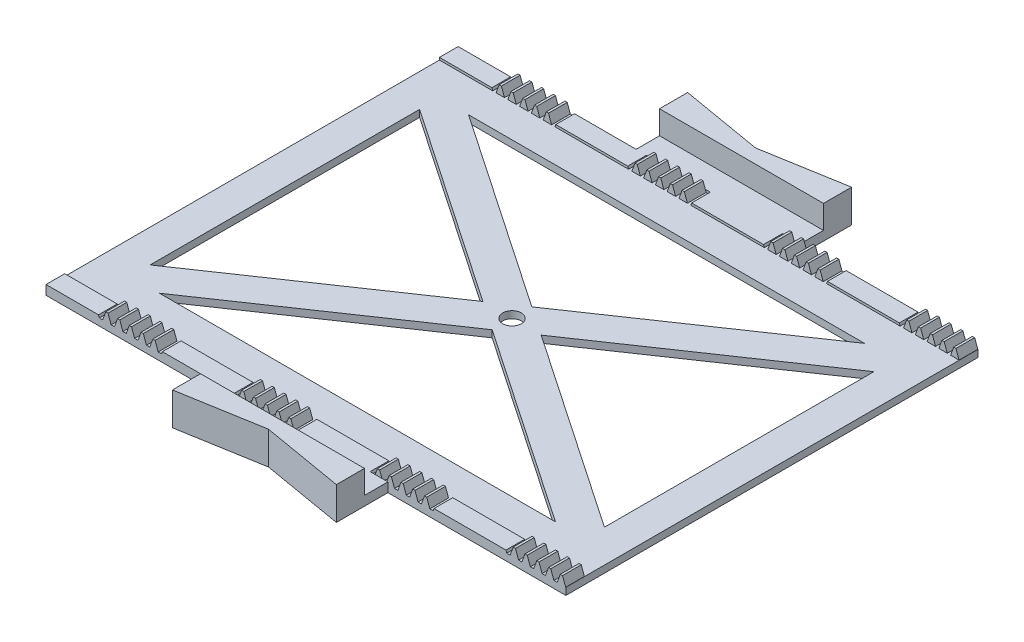
SolidWorks part; units mm, degrees
ref_plane "Front Plane" through (0, 0, 0) normal (0, 0, 1) x (1, 0, 0)
ref_plane "Top Plane" through (0, 0, 0) normal (0, 1, 0) x (1, 0, 0)
ref_plane "Right Plane" through (0, 0, 0) normal (1, 0, 0) x (0, 0, -1)
sketch "Sketch1" plane through (0, 0, 0) normal (0, 1, 0) x (1, 0, 0)
  line L0 (-17.5, -49) -> (-17.5, -44)
  line L1 (55.5, -44) -> (17.5, -44)
  line L2 (55.5, -44) -> (55.5, 44)
  line L3 (55.5, 44) -> (17.5, 44)
  line L4 (-55.5, -44) -> (-55.5, 44)
  line L5 (55.5, -44) -> (-55.5, 44) construction
  line L6 (55.5, 44) -> (-55.5, -44) construction
  line L7 (-17.5, -49) -> (17.5, -49)
  line L9 (17.5, -49) -> (17.5, -44)
  line L10 (-17.5, -49) -> (17.5, -44) construction
  line L11 (-17.5, -44) -> (17.5, -49) construction
  line L12 (0, -46.5) -> (0, 0) construction
  line L13 (-17.5, -44) -> (-55.5, -44)
  line L14 (0, 0) -> (-33.9675, 0) construction
  line L15 (-17.5, 44) -> (17.5, 49) construction
  line L16 (-17.5, 49) -> (17.5, 44) construction
  line L17 (17.5, 49) -> (17.5, 44)
  line L18 (-17.5, 49) -> (17.5, 49)
  line L19 (-17.5, 49) -> (-17.5, 44)
  line L20 (-17.5, 44) -> (-55.5, 44)
  point P0 (0, 0)
  point P7 (0, -46.5)
  dimension "D1" = 88
  dimension "D2" = 111
  dimension "D3" = 35
  dimension "D4" = 5
  dimension "D5" = 38
extrude "Boss-Extrude1" add sketch "Sketch1" along normal blind 2
sketch "Sketch7" plane through (0, 0, 44) normal (0, 0, 1) x (1, 0, 0)
  line L0 (46.111, 1.5) -> (45.4023, 1.5)
  line L1 (46.7754, 3.3254) -> (46.111, 1.5)
  line L2 (45.7566, 3.0029) -> (45.7566, 8.5) construction
  line L3 (46.7754, 3.3254) -> (44.7379, 3.3254)
  line L4 (55.5, 2) -> (55.5, 0) construction
  line L5 (17.5, 2) -> (55.5, 2) construction
  line L6 (44.7379, 3.3254) -> (45.4023, 1.5)
  line L9 (45.0383, 2.5) -> (46.475, 2.5) construction
  line L11 (46.475, 2.5) -> (46.475, 22.8524) construction
  line L12 (45.0383, 2.5) -> (45.0383, 22.8524) construction
  dimension "Pressure_angle" = 20
  dimension "Gap_width" = 1.4366
  dimension "Dedendum" = 1
  dimension "Addendum_plus" = 0.8254
  dimension "D1" = 9.7434
  dimension "D2" = 6.5
  dimension "D3" = 6
  dimension "D4" = 1.4366
sketch "Sketch8" plane through (0, 0, 44) normal (0, 0, 1) x (1, 0, 0)
  line L0 (17.5, 2) -> (55.5, 2) construction
  line L1 (55.8097, 2) -> (43.2434, 2)
  line L2 (55.8097, 2) -> (55.8097, 3.3254)
  line L3 (55.8097, 3.3254) -> (43.2434, 3.3254)
  line L4 (43.2434, 2) -> (43.2434, 3.3254)
  line L5 (45.7566, 3.0029) -> (45.7566, 8.5) construction
  line L6 (46.7754, 3.3254) -> (44.7379, 3.3254) construction
  dimension "D1" = 10.0531
  dimension "D2" = 2.5133
extrude "Boss-Extrude2" add sketch "Sketch8" against normal blind 4
extrude "Cut-Extrude1" cut sketch "Sketch7" against normal blind 4
pattern_linear "LPattern1" count 2 spacing 2.5133 along (-1, 0, 0) count 5 spacing 2.5133 along (1, 0, 0) of "Cut-Extrude1"
mirror "Mirror1" about plane through (0, 0, 0) normal (0, 0, 1) of "Boss-Extrude2", "LPattern1", "Cut-Extrude1"
pattern_linear "LPattern2" count 4 spacing 29 along (-1, 0, 0) of "Mirror1", "Boss-Extrude2", "Cut-Extrude1", "LPattern1"
sketch "Sketch9" plane through (0, 2, 0) normal (0, 1, 0) x (1, 0, 0)
  line L0 (55.5, -40) -> (55.5, 40) construction
  line L1 (55.5, 40) -> (-55.5, 40)
  line L2 (55.5, 40) -> (55.5, -40)
  line L3 (55.5, -40) -> (-55.5, -40)
  line L4 (-55.5, 40) -> (-55.5, -40)
  line L5 (-55.5, 44) -> (-55.5, -44) construction
  line L6 (55.4554, -40) -> (55.5, -40) construction
  line L7 (55.5, 40) -> (55.2734, 40) construction
extrude "Cut-Extrude2" cut sketch "Sketch9" against normal blind 0.5
sketch "Sketch10" plane through (0, 1.5, 0) normal (0, 1, 0) x (1, 0, 0)
  line L0 (42.2783, 33) -> (-48.5, -28.7666)
  line L1 (-48.5, -33) -> (48.5, -33)
  line L2 (-48.5, -33) -> (-48.5, 33)
  line L3 (-48.5, 33) -> (48.5, 33)
  line L4 (48.5, -33) -> (48.5, 33)
  line L5 (-48.5, -33) -> (48.5, 33) construction
  line L6 (-48.5, 33) -> (48.5, -33) construction
  line L7 (-1.9689, 2.8937) -> (1.9689, -2.8937) construction
  line L8 (-42.2783, -33) -> (48.5, 28.7666)
  line L9 (-48.5, 40) -> (-48.5, 33) construction
  line L10 (55.5, -40) -> (-55.5, -40)
  line L11 (55.5, -40) -> (55.5, 40)
  line L12 (55.5, 40) -> (-55.5, 40)
  line L13 (-55.5, -40) -> (-55.5, 40)
  line L14 (55.5, -40) -> (-55.5, 40) construction
  line L15 (55.5, 40) -> (-55.5, -40) construction
  line L16 (-48.5, 33) -> (-55.5, 33) construction
  line L17 (-48.5, 0) -> (48.5, 0) construction
  line L18 (42.2783, -33) -> (-48.5, 28.7666)
  line L19 (-42.2783, 33) -> (48.5, -28.7666)
  circle A0 centre (0, 0) radius 2
  point P0 (0, 0)
  point P12 (0, 0)
  dimension "D2" = 4
  dimension "D1" = 7
extrude "Cut-Extrude3" cut sketch "Sketch10" against normal through all contours L3 L19 L0 | L0 L18 L2 | L8 L19 L4 | L1 L18 L8 | A0
sketch "Sketch12" plane through (0, 0, 0) normal (0, 1, 0) x (1, 0, 0)
  line L0 (-17.5, -49) -> (-17.5, -55)
  line L1 (-17.5, -55) -> (0, -52)
  line L2 (0, -52) -> (17.5, -55)
  line L3 (17.5, -55) -> (17.5, -49)
  line L4 (-17.5, -49) -> (17.5, -49) construction
  line L5 (-17.5, -49) -> (17.5, -49)
  dimension "D1" = 3
  dimension "D2" = 6
extrude "Boss-Extrude3" add sketch "Sketch12" along normal blind 7
mirror "Mirror2" about plane through (0, 0, 0) normal (0, 0, 1) of "Boss-Extrude3"
sketch "Sketch13" plane through (0, 0, 0) normal (0, -1, 0) x (1, 0, 0)
  line L0 (55.5, 44) -> (55.5, -44) construction
  line L1 (17.5, 44) -> (55.5, 44) construction
  circle A0 centre (47.3, 36.3) radius 4
  dimension "D3" = 8
  dimension "D1" = 8.2
  dimension "D2" = 7.7
extrude "Cut-Extrude4" cut sketch "Sketch13" against normal blind 1
mirror "Mirror3" about plane through (0, 0, 0) normal (0, 0, 1) of "Cut-Extrude4"
mirror "Mirror4" about plane through (0, 0, 0) normal (1, 0, 0) of "Cut-Extrude4", "Mirror3"
equation "\"spa\"=24"
equation "\"D1@Sketch8\"=24/180*6*pi*4"
equation "\"D2@Sketch8\"=24/180*6*pi"
equation "\"D4@LPattern1\"=24/180*6*pi"
equation "\"D3@LPattern1\"=24/180*6*pi"
equation "\"D1@Sketch7\"=11mm-24/180*6*pi/2"
